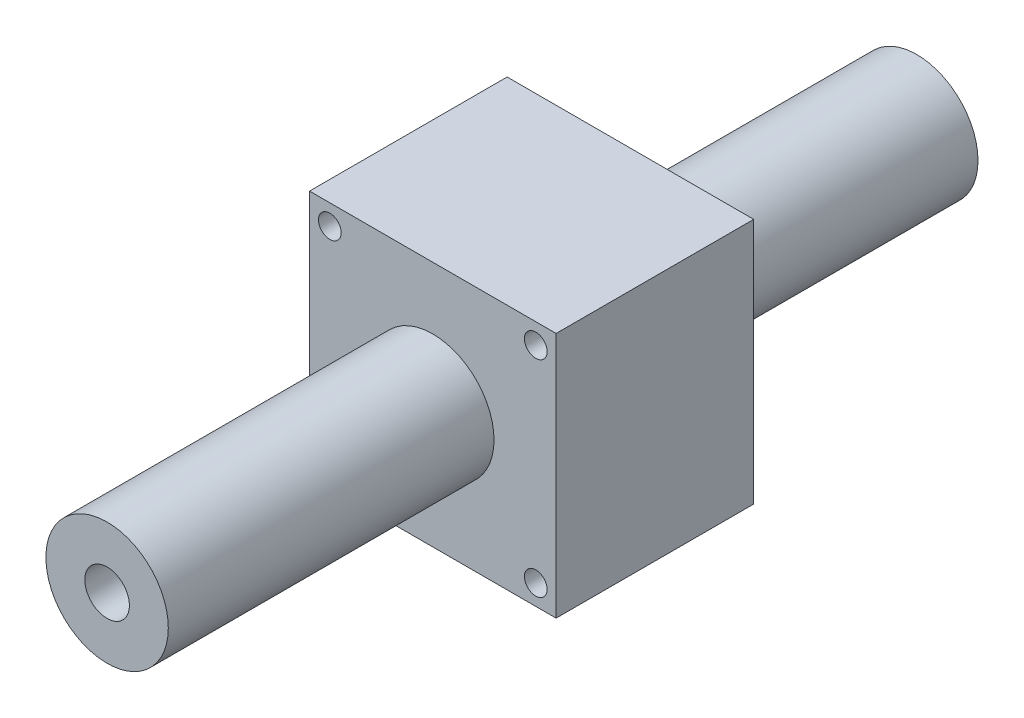
SolidWorks part; units mm, degrees
material "6061-T6 (SS)"
ref_plane "Front Plane" through (0, 0, 0) normal (0, 0, 1) x (1, 0, 0)
ref_plane "Top Plane" through (0, 0, 0) normal (0, 1, 0) x (1, 0, 0)
ref_plane "Right Plane" through (0, 0, 0) normal (1, 0, 0) x (0, 0, -1)
sketch "Sketch1" plane through (0, 0, 0) normal (0, 0, 1) x (1, 0, 0)
  line L1 (-28.2, -28.2) -> (28.2, -28.2)
  line L2 (-28.2, -28.2) -> (-28.2, 28.2)
  line L3 (-28.2, 28.2) -> (28.2, 28.2)
  line L4 (28.2, -28.2) -> (28.2, 28.2)
  circle A0 centre (-23.55, -23.55) radius 2.6
  circle A1 centre (-23.55, 23.55) radius 2.6
  circle A2 centre (23.55, -23.55) radius 2.6
  circle A3 centre (23.55, 23.55) radius 2.6
extrude "NA23_Motor_Envelope" add sketch "Sketch1" along normal blind 45.2 from offset 45.2
sketch "Sketch2" plane through (0, 0, 0) normal (0, 0, 1) x (1, 0, 0)
  circle A0 centre (0, 0) radius 14
extrude "Rear_Barrel_Envelope" add sketch "Sketch2" along normal blind 65.5 from offset 110.7
sketch "Sketch3" plane through (0, 0, 0) normal (0, 0, 1) x (1, 0, 0)
  circle A0 centre (0, 0) radius 14
  circle A1 centre (0, 0) radius 5.1
extrude "Fixed_Front_Barrel_Envelope" add sketch "Sketch3" along normal blind 74.5
